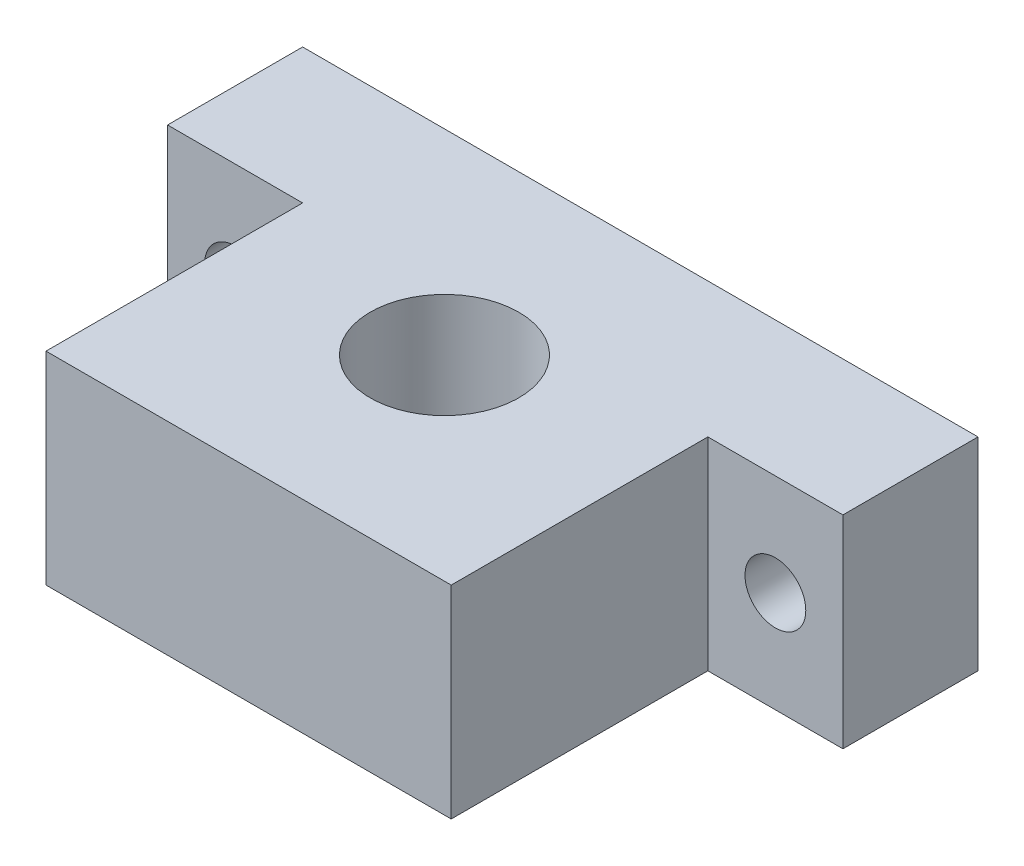
SolidWorks part; units mm, degrees
ref_plane "Front Plane" through (0, 0, 0) normal (0, 0, 1) x (1, 0, 0)
ref_plane "Top Plane" through (0, 0, 0) normal (0, 1, 0) x (1, 0, 0)
ref_plane "Right Plane" through (0, 0, 0) normal (1, 0, 0) x (0, 0, -1)
sketch "Sketch1" plane through (0, 2.5187, -29.699) normal (0, 0, 1) x (1, 0, 0)
  line L0 (-64.1266, 671.9676) -> (-14.1266, 671.9676)
  line L2 (-14.1266, 671.9676) -> (35.8734, 671.9676)
  line L3 (35.8734, 671.9676) -> (35.8734, 701.9676)
  line L4 (35.8734, 701.9676) -> (-64.1266, 701.9676)
  line L5 (-64.1266, 701.9676) -> (-64.1266, 671.9676)
  line L8 (-14.1266, 123.5532) -> (-14.1266, 923.5532) construction
  dimension "D1" = 100
  dimension "D2" = 30
extrude "Boss-Extrude1" add sketch "Sketch1" along normal up to surface (58 mm away)
sketch "Sketch3" plane through (0, 674.4863, 0) normal (0, -1, 0) x (1, 0, 0)
  circle A0 centre (-14.1266, -0.699) radius 11
  point P0 (-14.1266, -0.699)
  dimension "D1" = 22
extrude "Cut-Extrude1" cut sketch "Sketch3" against normal through all
sketch "Sketch4" plane through (0, 0, 28.301) normal (0, 0, 1) x (1, 0, 0)
  line L0 (-64.1266, 674.4863) -> (35.8734, 674.4863) construction
  line L1 (-64.1266, 704.4863) -> (-44.1266, 704.4863)
  line L2 (-64.1266, 704.4863) -> (-64.1266, 674.4863)
  line L3 (-64.1266, 674.4863) -> (-44.1266, 674.4863)
  line L4 (-44.1266, 704.4863) -> (-44.1266, 674.4863)
  line L5 (-14.1266, 704.4863) -> (-14.1266, 674.4863) construction
  line L6 (35.8734, 704.4863) -> (-64.1266, 704.4863) construction
  line L7 (15.8734, 704.4863) -> (15.8734, 674.4863)
  line L8 (35.8734, 674.4863) -> (15.8734, 674.4863)
  line L9 (35.8734, 704.4863) -> (35.8734, 674.4863)
  line L10 (35.8734, 704.4863) -> (15.8734, 704.4863)
  line L11 (-54.1266, 704.4863) -> (-54.1266, 674.4863) construction
  point P17 (-54.1266, 689.4863)
  point P18 (25.8734, 689.4863)
  dimension "D1" = 60
extrude "Cut-Extrude2" cut sketch "Sketch4" against normal offset from surface (38 mm away) 20 up to face at (-14.1266, 689.4863, -29.699)
hole_wizard "M8 Clearance Hole1" positions "Sketch5" profile "Sketch6" hole size "M8" standard "ISO"
sketch "Sketch5" plane through (-5.4221, 631.408, -9.699) normal (0, 0, 1) x (1, 0, 0)
  point P0 (-48.7044, -458.8361)
  point P3 (-48.7044, -493.8361)
  point P6 (31.2956, -458.8361)
  point P9 (31.2956, -493.8361)
  point P12 (-48.7044, 58.0784)
  point P15 (31.2956, 58.0784)
sketch "Sketch6" plane through (-54.1266, 172.5718, -9.699) normal (1, 0, 0) x (0, -1, 0)
  line L0 (0, 0) -> (0, 22.7029)
  line L1 (0, 22.7029) -> (4.5, 19.999)
  line L2 (4.5, 19.999) -> (4.5, 0)
  line L3 (4.5, 0) -> (0, 0)
  line L4 (0, 22.7029) -> (-4.5, 19.999) construction
  line L5 (0, -6.35) -> (0, 107.95) construction
  dimension "Hole Dia." = 9
  dimension "Hole Depth" = 19.999
  dimension "Drill Angle" = 118
